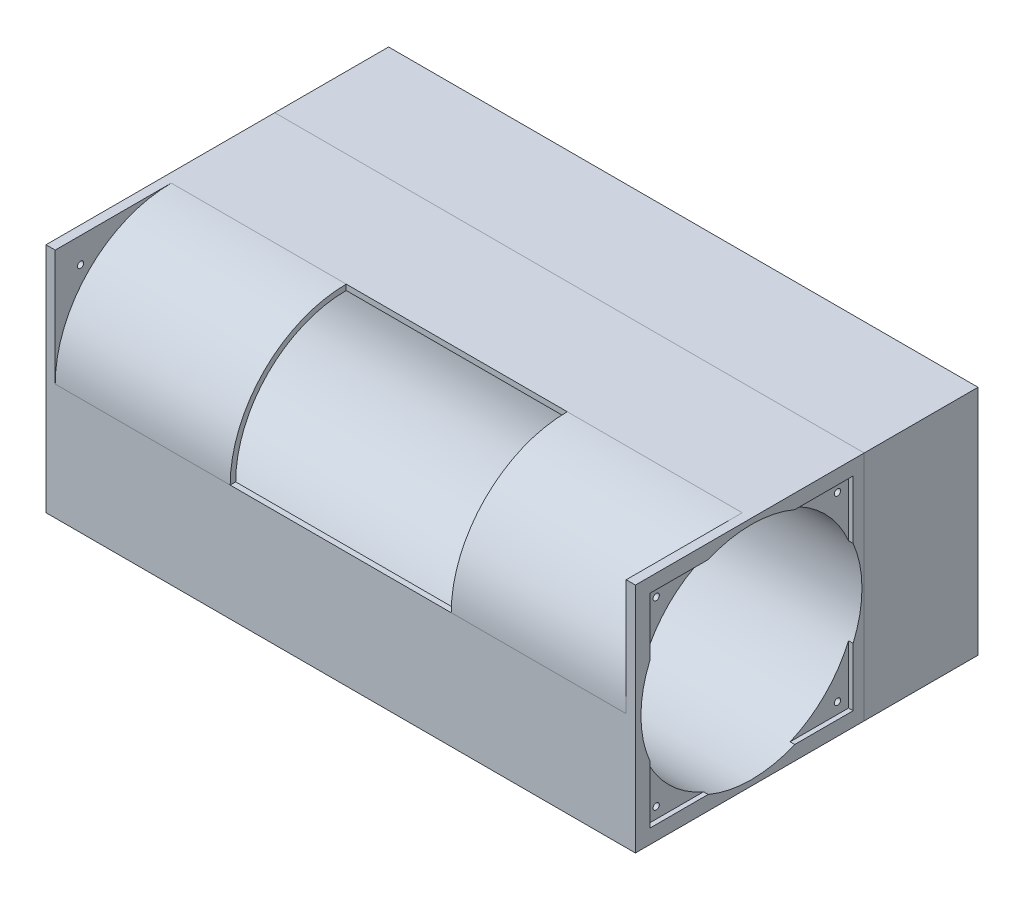
SolidWorks part; units mm, degrees
other "Main Case"
material "PLA"
ref_plane "Front Plane" through (0, 0, 0) normal (0, 0, 1) x (1, 0, 0)
ref_plane "Top Plane" through (0, 0, 0) normal (0, 1, 0) x (1, 0, 0)
ref_plane "Right Plane" through (0, 0, 0) normal (1, 0, 0) x (0, 0, -1)
sketch "Sketch7" plane through (0, 0, 0) normal (1, 0, 0) x (0, 0, -1)
  line L1 (-80.01, 80.01) -> (80.01, 80.01)
  line L2 (-80.01, 80.01) -> (-80.01, -80.01)
  line L3 (-80.01, -80.01) -> (80.01, -80.01)
  line L4 (80.01, 80.01) -> (80.01, -80.01)
  line L5 (-80.01, 80.01) -> (80.01, -80.01) construction
  line L6 (-80.01, -80.01) -> (80.01, 80.01) construction
  point P0 (0, 0)
  dimension "D1" = 160.02
  dimension "D2" = 160.02
extrude "Boss-Extrude4" add sketch "Sketch7" along normal mid plane 406.4
sketch "Sketch8" plane through (0, 0, 0) normal (1, 0, 0) x (0, 0, -1)
  line L0 (-80.01, 80.01) -> (-80.01, -80.01) construction
  line L1 (80.01, 80.01) -> (-80.01, 80.01) construction
  line L2 (-80.01, 80.01) -> (-80.01, 0)
  line L3 (0, 80.01) -> (-80.01, 80.01)
  arc A0 (0, 80.01) -> (-80.01, 0) centre (0, 0) ccw
  dimension "D1" = 160.02
extrude "Cut-Extrude3" cut sketch "Sketch8" against normal mid plane 393.7
sketch "Sketch9" plane through (203.2, 0, 0) normal (1, 0, 0) x (0, 0, -1)
  circle A0 centre (0, 0) radius 76.2
  dimension "D1" = 152.4
extrude "Cut-Extrude4" cut sketch "Sketch9" against normal through all
sketch "Sketch10" plane through (203.2, 0, 0) normal (1, 0, 0) x (0, 0, -1)
  line L1 (-70.104, 70.104) -> (70.104, 70.104)
  line L2 (-70.104, 70.104) -> (-70.104, -70.104)
  line L3 (-70.104, -70.104) -> (70.104, -70.104)
  line L4 (70.104, 70.104) -> (70.104, -70.104)
  line L5 (-70.104, 70.104) -> (70.104, -70.104) construction
  line L6 (-70.104, -70.104) -> (70.104, 70.104) construction
  point P0 (0, 0)
  dimension "D1" = 140.208
  dimension "D2" = 140.208
extrude "Cut-Extrude5" cut sketch "Sketch10" against normal blind 3.175
sketch "Sketch11" plane through (0, 0, 80.01) normal (0, 0, 1) x (1, 0, 0)
  line L0 (-76.2, 0) -> (76.2, 0)
  line L1 (-196.85, 0) -> (196.85, 0) construction
  line L2 (76.2, 0) -> (76.2, 80.01)
  line L3 (-196.85, 80.01) -> (196.85, 80.01) construction
  line L4 (76.2, 80.01) -> (-76.2, 80.01)
  line L5 (-76.2, 80.01) -> (-76.2, 0)
  point P5 (0, 0)
  dimension "D1" = 152.4
extrude "Cut-Extrude6" cut sketch "Sketch11" against normal blind 80.01
sketch "Sketch12" plane through (-76.2, 0, 0) normal (1, 0, 0) x (0, 0, -1)
  line L0 (-76.2, 0) -> (-80.01, 0) construction
  line L1 (0, 80.01) -> (0, 76.2) construction
  line L2 (-76.2, 0) -> (-80.01, 0)
  line L3 (0, 80.01) -> (0, 76.2)
  arc A0 (0, 76.2) -> (-76.2, 0) centre (0, 0) ccw construction
  arc A1 (0, 80.01) -> (-80.01, 0) centre (0, 0) ccw construction
  arc A2 (0, 76.2) -> (-76.2, 0) centre (0, 0) ccw
  arc A3 (0, 80.01) -> (-80.01, 0) centre (0, 0) ccw
mirror "Mirror1" about plane through (0, 0, 0) normal (1, 0, 0) of "Cut-Extrude5"
sketch "Sketch13" plane through (0, 0, -80.01) normal (0, 0, -1) x (-1, 0, 0)
  line L0 (-203.2, -80.01) -> (203.2, -80.01) construction
  line L1 (203.2, -80.01) -> (203.2, 80.01) construction
  line L2 (-203.2, -80.01) -> (-203.2, 80.01) construction
  line L3 (-203.2, 80.01) -> (203.2, 80.01) construction
  line L4 (-203.2, -80.01) -> (203.2, -80.01)
  line L5 (203.2, -80.01) -> (203.2, 80.01)
  line L6 (-203.2, -80.01) -> (-203.2, 80.01)
  line L7 (-203.2, 80.01) -> (203.2, 80.01)
extrude "Boss-Extrude6" add sketch "Sketch13" along normal blind 76.2
sketch "Sketch15" plane through (0, 0, 0) normal (1, 0, 0) x (0, 0, -1)
  line L0 (81.534, 76.2) -> (81.534, -76.2)
  line L1 (81.534, -76.2) -> (156.21, -76.2)
  line L2 (156.21, -76.2) -> (156.21, 76.2)
  line L3 (156.21, 76.2) -> (81.534, 76.2)
  line L4 (70.104, 29.8642) -> (70.104, 70.104) construction
  line L5 (156.21, 80.01) -> (156.21, -80.01) construction
  point P4 (118.872, -76.2)
  point P7 (81.534, 0)
  dimension "D2" = 11.43
  dimension "D3" = 152.4
extrude "Cut-Extrude7" cut sketch "Sketch15" against normal mid plane 400.05
sketch "Sketch16" plane through (200.025, 0, 0) normal (1, 0, 0) x (0, 0, -1)
  line L0 (0, -80.01) -> (0, 80.01) construction
  circle A1 centre (-62.5, 62.5) radius 2.15
  circle A2 centre (62.5, 62.5) radius 2.15
  circle A3 centre (-62.5, -62.5) radius 2.15
  circle A4 centre (62.5, -62.5) radius 2.15
  point P5 (0, 0)
  dimension "D1" = 125
  dimension "D3" = 4.3
  dimension "D2" = 125
  dimension "D4" = 62.5
extrude "Cut-Extrude8" cut sketch "Sketch16" against normal through all
ref_plane "Plane1" through (0, 0, -77.724) normal (0, 0, -1) x (-1, 0, 0)
split "Split1" trim tools "Plane1" bodies to split 119 resulting bodies 120 121
